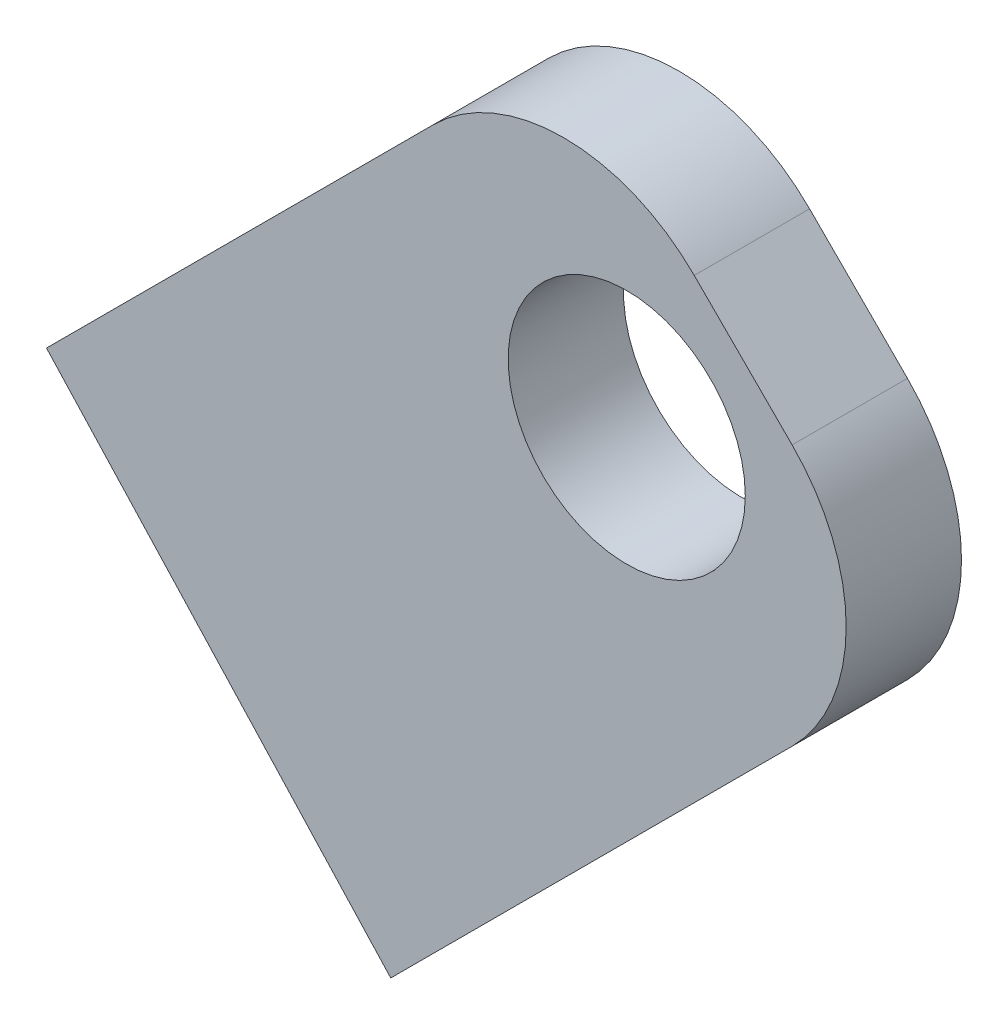
SolidWorks part; units mm, degrees
ref_plane "Front Plane" through (0, 0, 0) normal (0, 0, 1) x (1, 0, 0)
ref_plane "Top Plane" through (0, 0, 0) normal (0, 1, 0) x (1, 0, 0)
ref_plane "Right Plane" through (0, 0, 0) normal (1, 0, 0) x (0, 0, -1)
sketch "Sketch1" plane through (0, 0, 0) normal (0, 0, 1) x (1, 0, 0)
  line L0 (-1.5305, -11.2078) -> (9.5189, -0.1584)
  line L1 (9.5189, 7.0258) -> (6.8249, 9.7199)
  line L2 (-0.3594, 9.7199) -> (-11.0068, -0.9276)
  line L3 (-11.0068, -0.9276) -> (-1.5305, -11.2078)
  line L4 (8.1719, 8.3729) -> (-6.2687, -6.0677) construction
  line L5 (0.9516, 1.1526) -> (5.8907, -3.7865) construction
  line L6 (0.9516, 1.1526) -> (-3.9875, 6.0917) construction
  circle A0 centre (4.9659, 5.1669) radius 3.2639
  arc A1 (6.8249, 9.7199) -> (-0.3594, 9.7199) centre (3.2327, 6.1278) ccw
  arc A2 (9.5189, -0.1584) -> (9.5189, 7.0258) centre (5.9268, 3.4337) ccw
  dimension "D2" = 6.5278
  dimension "D5" = 5.08
  dimension "D1" = 13.97
  dimension "D3" = 4.5339
  dimension "D4" = 15.875
extrude "Boss-Extrude1" add sketch "Sketch1" along normal blind 3.175
